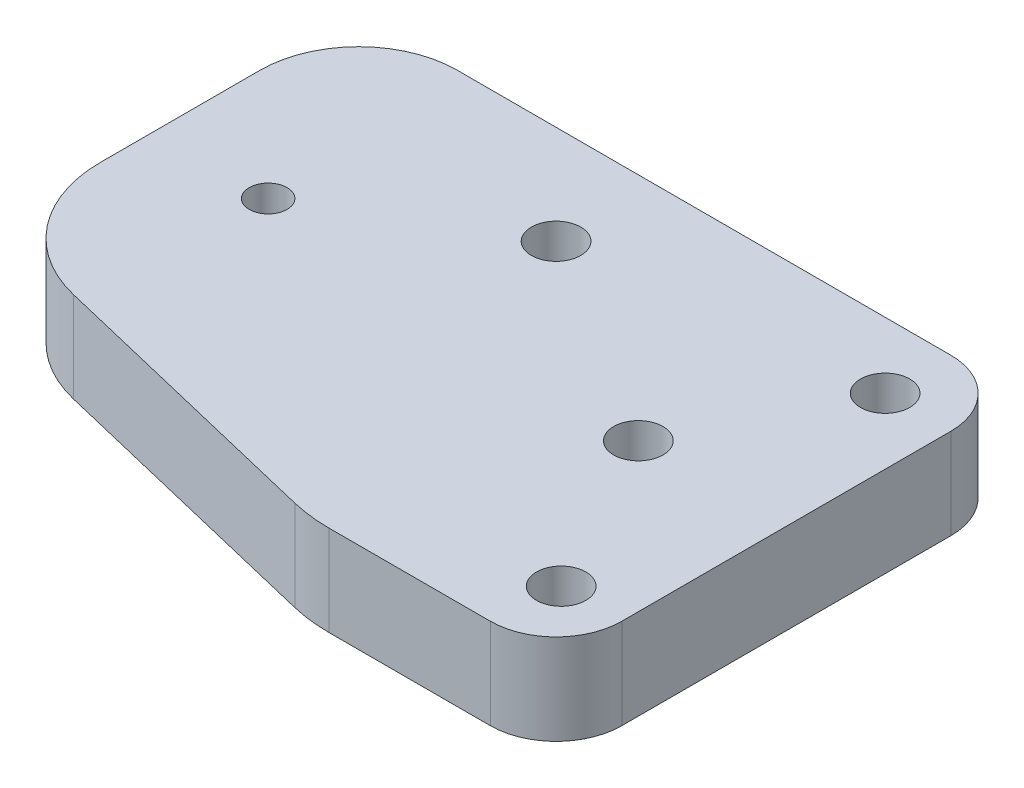
SolidWorks part; units mm, degrees
ref_plane "Front Plane" through (0, 0, 0) normal (0, 0, 1) x (1, 0, 0)
ref_plane "Top Plane" through (0, 0, 0) normal (0, 1, 0) x (1, 0, 0)
ref_plane "Right Plane" through (0, 0, 0) normal (1, 0, 0) x (0, 0, -1)
sketch "Sketch1" plane through (0, 0, 0) normal (0, 1, 0) x (1, 0, 0)
  line L0 (0, 16) -> (25, 10)
  line L1 (25, 10) -> (40, 10)
  line L2 (0, 16) -> (0, 38)
  line L3 (0, 38) -> (40, 38)
  line L4 (40, 10) -> (40, 38)
  circle A0 centre (36, 34) radius 1.5
  circle A1 centre (36.3112, 14) radius 1.5
  circle A2 centre (31, 24) radius 1.5
  circle A3 centre (18, 32) radius 1.5
  circle A4 centre (7, 25.5) radius 1.15
  dimension "D3" = 3
  dimension "D4" = 3
  dimension "D5" = 3
  dimension "D11" = 3
  dimension "D17" = 2.3
  dimension "D1" = 28
  dimension "D2" = 40
  dimension "D6" = 4
  dimension "D7" = 4
  dimension "D8" = 20
  dimension "D9" = 9
  dimension "D10" = 14
  dimension "D12" = 22
  dimension "D13" = 6
  dimension "D16" = 12.5
  dimension "D18" = 7
extrude "Boss-Extrude1" add sketch "Sketch1" along normal blind 5.5
fillet "Fillet1" radius 6 1 edges at (0, 2.75, -38)
fillet "Fillet2" radius 8 1 edges at (0, 2.75, -16)
fillet "Fillet3" radius 4 1 edges at (40, 2.75, -38)
fillet "Fillet4" radius 4 1 edges at (40, 2.75, -10)
fillet "Fillet5" radius 10 1 edges at (25, 2.75, -10)
